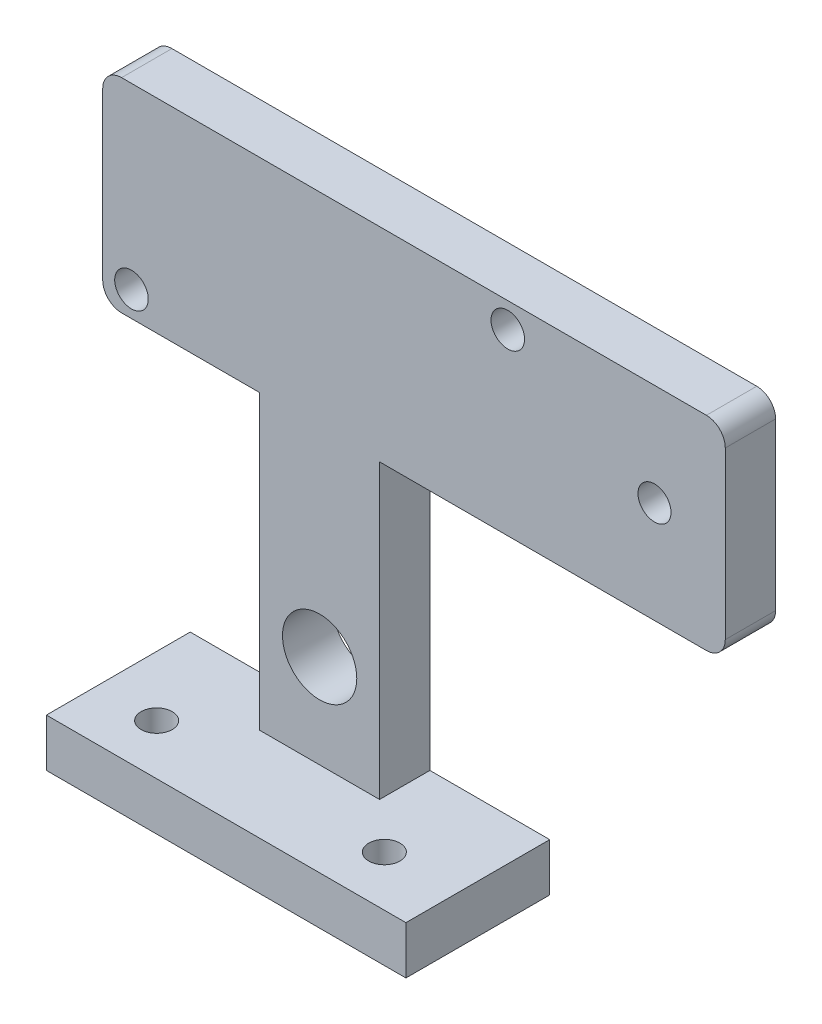
SolidWorks part; units mm, degrees
ref_plane "Front Plane" through (0, 0, 0) normal (0, 0, 1) x (1, 0, 0)
ref_plane "Top Plane" through (0, 0, 0) normal (0, 1, 0) x (1, 0, 0)
ref_plane "Right Plane" through (0, 0, 0) normal (1, 0, 0) x (0, 0, -1)
sketch "Sketch1" plane through (0, 0, 0) normal (0, 1, 0) x (1, 0, 0)
  line L1 (-100.9616, 61.8132) -> (-62.8616, 61.8132)
  line L2 (-100.9616, 61.8132) -> (-100.9616, 46.5732)
  line L3 (-100.9616, 46.5732) -> (-62.8616, 46.5732)
  line L4 (-62.8616, 61.8132) -> (-62.8616, 46.5732)
  dimension "D1" = 38.1
  dimension "D2" = 15.24
extrude "Boss-Extrude1" add sketch "Sketch1" against normal blind 5.08
sketch "Sketch2" plane through (0, 0, 0) normal (0, 1, 0) x (1, 0, 0)
  line L0 (-62.8616, 61.8132) -> (-100.9616, 61.8132) construction
  line L1 (-94.6116, 51.9072) -> (-102.2316, 51.9072) construction
  line L2 (-62.8616, 46.5732) -> (-62.8616, 61.8132) construction
  line L6 (-70.4816, 51.9072) -> (-62.8616, 51.9072) construction
  circle A0 centre (-94.6116, 51.9072) radius 1.651
  circle A1 centre (-70.4816, 51.9072) radius 1.651
  dimension "D1" = 3.302
  dimension "D2" = 24.13
  dimension "D3" = 9.906
extrude "Cut-Extrude1" cut sketch "Sketch2" against normal through all
sketch "Sketch3" plane through (0, 0, 0) normal (0, 1, 0) x (1, 0, 0)
  line L0 (-62.8616, 61.8132) -> (-100.9616, 61.8132) construction
  line L1 (-88.2616, 61.8132) -> (-75.5616, 61.8132)
  line L2 (-88.2616, 61.8132) -> (-88.2616, 56.4792)
  line L3 (-88.2616, 56.4792) -> (-75.5616, 56.4792)
  line L4 (-75.5616, 61.8132) -> (-75.5616, 56.4792)
  line L5 (-88.2616, 61.8132) -> (-100.9616, 61.8132) construction
  line L6 (-75.5616, 61.8132) -> (-62.8616, 61.8132) construction
  dimension "D1" = 5.334
  dimension "D2" = 12.7
extrude "Boss-Extrude2" add sketch "Sketch3" along normal blind 30.988
sketch "Sketch6" plane through (0, 30.988, 0) normal (0, 1, 0) x (1, 0, 0)
  line L0 (-75.5616, 56.4792) -> (-75.5616, 61.8132) construction
  line L1 (-104.8986, 61.8132) -> (-58.9246, 61.8132)
  line L2 (-104.8986, 61.8132) -> (-104.8986, 56.4792)
  line L3 (-104.8986, 56.4792) -> (-58.9246, 56.4792)
  line L4 (-58.9246, 61.8132) -> (-58.9246, 56.4792)
  line L5 (-104.8986, 61.8132) -> (-88.2616, 61.8132) construction
  line L6 (-75.5616, 61.8132) -> (-58.9246, 61.8132) construction
  dimension "D1" = 45.974
extrude "Boss-Extrude3" add sketch "Sketch6" along normal blind 21.59
sketch "Sketch7" plane through (0, 0, -56.4792) normal (0, 0, 1) x (1, 0, 0)
  line L0 (-61.9726, 49.911) -> (-58.9246, 49.911) construction
  line L1 (-58.9246, 52.578) -> (-58.9246, 30.988) construction
  line L2 (-101.8506, 33.655) -> (-104.8986, 33.655) construction
  line L3 (-104.8986, 52.578) -> (-104.8986, 30.988) construction
  line L4 (-101.8506, 33.655) -> (-101.8506, 30.988) construction
  line L5 (-104.8986, 30.988) -> (-88.2616, 30.988) construction
  line L6 (-61.9726, 49.911) -> (-61.9726, 52.578) construction
  line L7 (-104.8986, 52.578) -> (-58.9246, 52.578) construction
  circle A0 centre (-101.8506, 33.655) radius 1.778
  circle A1 centre (-61.9726, 49.911) radius 1.778
  dimension "D1" = 3.556
  dimension "D2" = 39.878
  dimension "D3" = 16.256
extrude "Cut-Extrude4" cut sketch "Sketch7" against normal through all
sketch "Sketch8" plane through (0, 0, -56.4792) normal (0, 0, 1) x (1, 0, 0)
  line L0 (-88.2616, 9.906) -> (-81.9116, 9.906) construction
  line L1 (-88.2616, 30.988) -> (-88.2616, 0) construction
  line L2 (-81.9116, 9.906) -> (-75.5616, 9.906) construction
  line L3 (-75.5616, 30.988) -> (-75.5616, 0) construction
  line L4 (-75.5616, 30.988) -> (-58.9246, 30.988) construction
  circle A0 centre (-81.9116, 9.906) radius 3.937
  dimension "D2" = 7.874
  dimension "D1" = 21.082
extrude "Cut-Extrude5" cut sketch "Sketch8" against normal through all
sketch "Sketch9" plane through (-58.9246, 0, 0) normal (1, 0, 0) x (0, 0, -1)
  line L1 (56.4792, 30.988) -> (61.8132, 30.988)
  line L2 (56.4792, 30.988) -> (56.4792, 52.578)
  line L3 (56.4792, 52.578) -> (61.8132, 52.578)
  line L4 (61.8132, 30.988) -> (61.8132, 52.578)
extrude "Boss-Extrude4" add sketch "Sketch9" along normal blind 20
sketch "Sketch10" plane through (0, 0, -56.4792) normal (0, 0, 1) x (1, 0, 0)
  line L0 (-38.9246, 52.578) -> (-38.9246, 30.988) construction
  line L1 (-46.4246, 41.783) -> (-38.9246, 41.783) construction
  circle A0 centre (-46.4246, 41.783) radius 1.75
  dimension "D1" = 3.5
  dimension "D2" = 7.5
extrude "Cut-Extrude6" cut sketch "Sketch10" against normal through all
fillet "Fillet1" radius 2 2 edges at (-38.9246, 30.988, -59.1462) (-38.9246, 52.578, -59.1462)
fillet "Fillet2" radius 2 2 edges at (-104.8986, 30.988, -59.1462) (-104.8986, 52.578, -59.1462)
